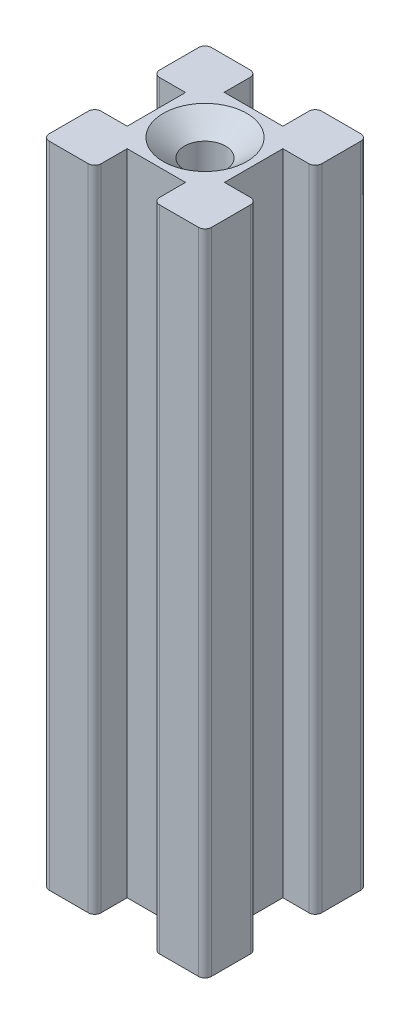
SolidWorks part; units mm, degrees
ref_plane "Front Plane" through (0, 0, 0) normal (0, 0, 1) x (1, 0, 0)
ref_plane "Top Plane" through (0, 0, 0) normal (0, 1, 0) x (1, 0, 0)
ref_plane "Right Plane" through (0, 0, 0) normal (1, 0, 0) x (0, 0, -1)
sketch "Sketch1" plane through (0, 0, 0) normal (0, 1, 0) x (1, 0, 0)
  line L1 (-12.5, -12.5) -> (12.5, -12.5)
  line L2 (-12.5, -12.5) -> (-12.5, 12.5)
  line L3 (-12.5, 12.5) -> (12.5, 12.5)
  line L4 (12.5, -12.5) -> (12.5, 12.5)
  line L5 (-12.5, -12.5) -> (12.5, 12.5) construction
  line L6 (-12.5, 12.5) -> (12.5, -12.5) construction
  point P0 (0, 0)
  dimension "D1" = 25
  dimension "D2" = 25
extrude "Boss-Extrude1" add sketch "Sketch1" along normal blind 100
sketch "Sketch2" plane through (0, 100, 0) normal (0, 1, 0) x (1, 0, 0)
  line L5 (-12.5, 12.5) -> (-12.5, -12.5) construction
  line L6 (-12.5, -4.5) -> (-7.5, -4.5)
  line L7 (-12.5, -12.5) -> (12.5, -12.5) construction
  line L8 (-4.5, -12.5) -> (4.5, -12.5)
  line L9 (-4.5, -12.5) -> (-4.5, -7.5)
  line L10 (-4.5, -7.5) -> (4.5, -7.5)
  line L11 (4.5, -12.5) -> (4.5, -7.5)
  line L12 (-12.5, -4.5) -> (-12.5, 4.5)
  line L13 (-12.5, 4.5) -> (-7.5, 4.5)
  line L14 (-7.5, -4.5) -> (-7.5, 4.5)
  line L15 (12.5, 12.5) -> (-12.5, 12.5) construction
  line L16 (-4.5489, 12.5) -> (4.5, 12.5)
  line L17 (-4.5489, 12.5) -> (-4.5489, 7.5)
  line L18 (-4.5489, 7.5) -> (4.5, 7.5)
  line L19 (4.5, 12.5) -> (4.5, 7.5)
  line L20 (12.5, -12.5) -> (12.5, 12.5) construction
  line L21 (12.5, 4.5) -> (7.5, 4.5)
  line L22 (12.5, 4.5) -> (12.5, -4.5)
  line L23 (12.5, -4.5) -> (7.5, -4.5)
  line L24 (7.5, 4.5) -> (7.5, -4.5)
  dimension "D1" = 5
  dimension "D2" = 5
  dimension "D3" = 5
  dimension "D4" = 5
  dimension "D5" = 8
  dimension "D6" = 8
  dimension "D7" = 8
  dimension "D8" = 8
  dimension "D9" = 8
  dimension "D10" = 8
  dimension "D11" = 8
ref_plane "Plane1" through (-12.5, 100, -12.5) normal (0, -1, 0) x (-1, 0, 0)
extrude "Cut-Extrude1" cut sketch "Sketch2" against normal blind 100
fillet "Fillet1" radius 1 12 edges at (4.5, 50, -12.5) (12.5, 50, -12.5) (12.5, 50, -4.5) (12.5, 50, 4.5) (12.5, 50, 12.5) (4.5, 50, 12.5) (-4.5, 50, 12.5) (-12.5, 50, 12.5) (-12.5, 50, 4.5) (-12.5, 50, -4.5) (-12.5, 50, -12.5) (-4.5489, 50, -12.5)
sketch "Sketch4" plane through (0, 100, 0) normal (0, 1, 0) x (1, 0, 0)
  point P0 (0, 0)
hole_wizard "1/4 (0.25) Diameter Hole1" positions "Sketch5" profile "Sketch6" hole size "1/4" standard "ANSI Inch" end condition up to next
sketch "Sketch5" plane through (0, 100, 0) normal (0, 1, 0) x (1, 0, 0)
  point P0 (0, 0)
sketch "Sketch6" plane through (0, 100, 0) normal (1, 0, 0) x (0, 0, 1)
  line L0 (0, 0) -> (0, 100)
  line L1 (0, 100) -> (3.175, 100)
  line L2 (3.175, 100) -> (3.175, 2.7387)
  line L3 (3.175, 2.7387) -> (6.4389, 0)
  line L5 (6.4389, 0) -> (0, 0)
  line L6 (-3.175, 2.7387) -> (-6.4389, 0) construction
  line L11 (0, -6.35) -> (0, 107.95) construction
  dimension "Thru Hole Dia." = 6.35
  dimension "Thru Hole Depth" = 100
  dimension "Near C'Sink Dia." = 12.8778
  dimension "Near C'Sink Angle" = 100
